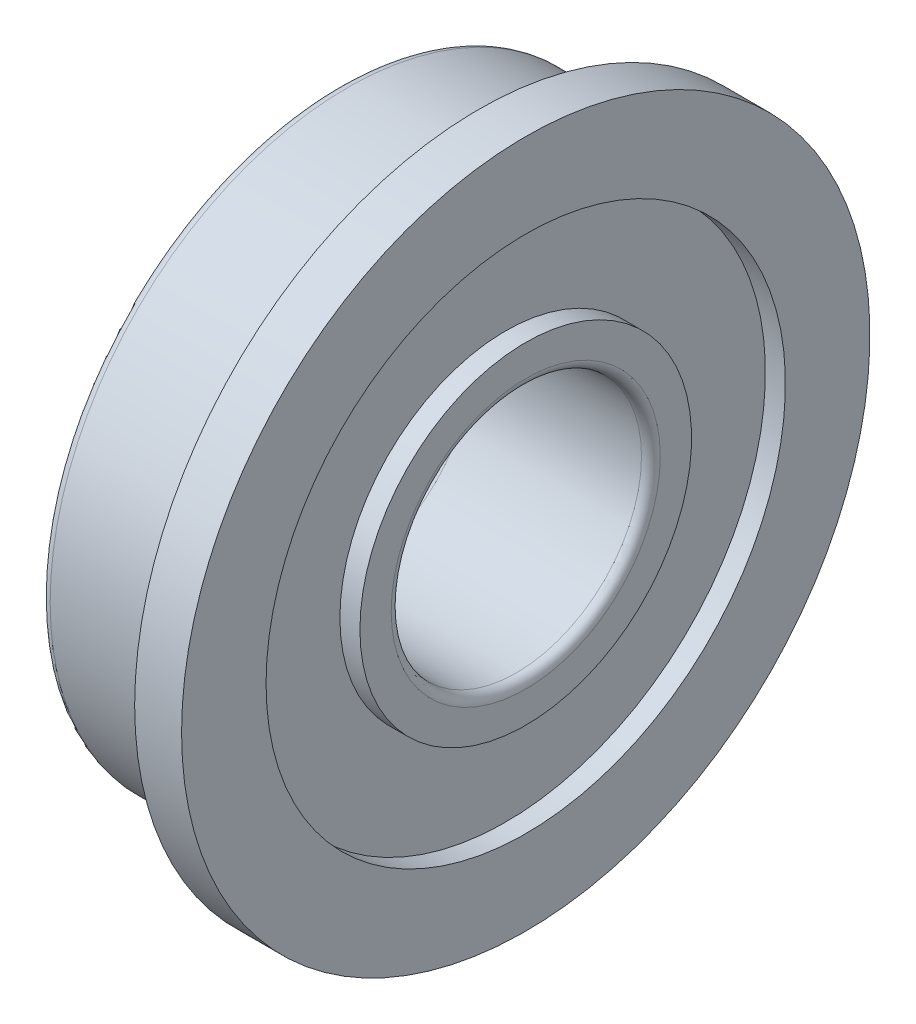
SolidWorks part; units mm, degrees
ref_plane "Front Plane" through (0, 0, 0) normal (0, 0, 1) x (1, 0, 0)
ref_plane "Top Plane" through (0, 0, 0) normal (0, 1, 0) x (1, 0, 0)
ref_plane "Right Plane" through (0, 0, 0) normal (1, 0, 0) x (0, 0, -1)
ref_plane "Plane1" through (0, 0, 0) normal (0, 0, 1) x (1, 0, 0)
sketch "Sketch1" plane through (0, 0, 0) normal (0, 0, 1) x (1, 0, 0)
  line L0 (0, 9.2) -> (0, 8.3)
  line L1 (0, 8.3) -> (0.64, 8.3)
  line L2 (0.64, 8.3) -> (0.64, 5.3)
  line L3 (0.64, 5.3) -> (0, 5.3)
  line L4 (0, 5.3) -> (0, 4.3)
  line L5 (0.3, 4) -> (5.7, 4)
  line L6 (6, 4.3) -> (6, 5.3)
  line L7 (6, 5.3) -> (5.36, 5.3)
  line L8 (5.36, 5.3) -> (5.36, 8.3)
  line L9 (5.36, 8.3) -> (6, 8.3)
  line L10 (6, 8.3) -> (6, 11)
  line L11 (6, 11) -> (4.5, 11)
  line L12 (4.5, 11) -> (4.5, 9.8)
  line L13 (4.2, 9.5) -> (0.3, 9.5)
  line L14 (19, 0) -> (-19, 0) construction
  arc A0 (0, 4.3) -> (0.3, 4) centre (0.3, 4.3) ccw
  arc A1 (5.7, 4) -> (6, 4.3) centre (5.7, 4.3) ccw
  arc A2 (4.5, 9.8) -> (4.2, 9.5) centre (4.5, 9.5) cw
  arc A3 (0.3, 9.5) -> (0, 9.2) centre (0.3, 9.2) ccw
revolve "Revolve1" add sketch "Sketch1" angle 360 about L14
